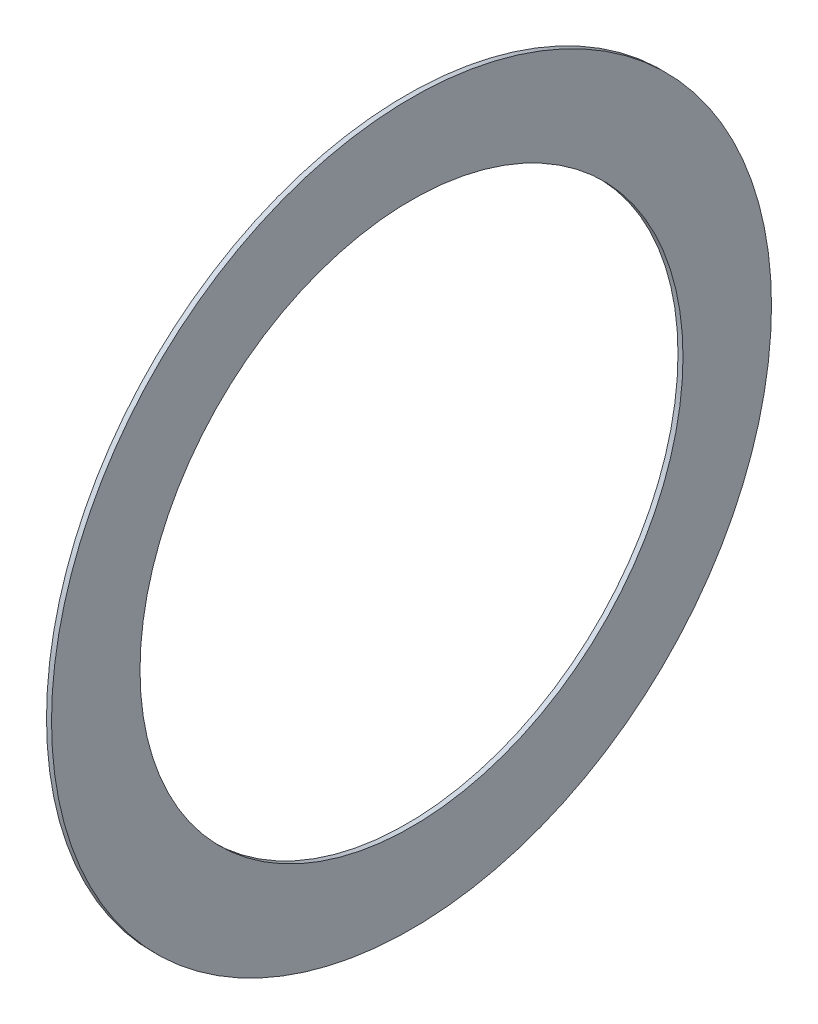
SolidWorks part; units mm, degrees
ref_plane "Front Plane" through (0, 0, 0) normal (0, 0, 1) x (1, 0, 0)
ref_plane "Top Plane" through (0, 0, 0) normal (0, 1, 0) x (1, 0, 0)
ref_plane "Right Plane" through (0, 0, 0) normal (1, 0, 0) x (0, 0, -1)
sketch "Sketch1" plane through (0, 0, 0) normal (1, 0, 0) x (0, 0, -1)
  circle A0 centre (0, 0) radius 36
  circle A1 centre (0, 0) radius 27.15
  dimension "D1" = 72
  dimension "D2" = 54.3
extrude "Boss-Extrude1" add sketch "Sketch1" along normal blind 0.5
